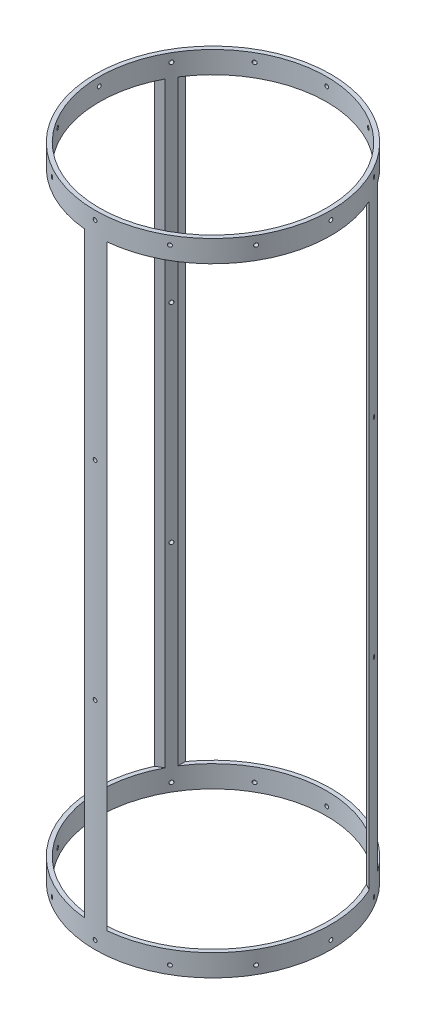
SolidWorks part; units mm, degrees
material "6061-T6 (SS)"
ref_plane "Front Plane" through (0, 0, 0) normal (0, 0, 1) x (1, 0, 0)
ref_plane "Top Plane" through (0, 0, 0) normal (0, 1, 0) x (1, 0, 0)
ref_plane "Right Plane" through (0, 0, 0) normal (1, 0, 0) x (0, 0, -1)
sketch "Sketch1" plane through (0, 0, 0) normal (0, 1, 0) x (1, 0, 0)
  circle A0 centre (0, 0) radius 88.9
  circle A1 centre (0, 0) radius 85.725
  dimension "D1" = 177.8
  dimension "D2" = 171.45
extrude "Boss-Extrude1" add sketch "Sketch1" along normal mid plane 482.854
sketch "Sketch2" plane through (0, 0, 0) normal (0, 0, 1) x (1, 0, 0)
  line L0 (85.725, 241.427) -> (-85.725, 241.427) construction
  line L1 (-72.39, -224.917) -> (72.39, -224.917)
  line L2 (-72.39, -224.917) -> (-72.39, 224.917)
  line L3 (-72.39, 224.917) -> (72.39, 224.917)
  line L4 (72.39, -224.917) -> (72.39, 224.917)
  line L5 (-72.39, -224.917) -> (72.39, 224.917) construction
  line L6 (-72.39, 224.917) -> (72.39, -224.917) construction
  line L7 (88.9, -241.427) -> (88.9, 241.427) construction
  point P0 (0, 0)
  dimension "D1" = 16.51
  dimension "D2" = 16.51
extrude "Cut-Extrude1" cut sketch "Sketch2" against normal up to surface (51.6033 mm away)
pattern_circular "CirPattern1" count 3 over 360 about axis through (0, 0, 0) along (0, 1, 0) of "Cut-Extrude1"
ref_plane "Plane1" through (88.9, 0, 0) normal (1, 0, 0) x (0, 0, -1)
sketch "Sketch4" plane through (88.9, 0, 0) normal (1, 0, 0) x (0, 0, -1)
  line L0 (0, 97.79) -> (0, -97.79) construction
  line L1 (88.9, 241.427) -> (-88.9, 241.427) construction
  circle A0 centre (0, 235.077) radius 1.4351
  dimension "D1" = 2.8702
  dimension "D2" = 6.35
extrude "Cut-Extrude3" cut sketch "Sketch4" against normal blind 15.24
pattern_circular "CirPattern3" count 12 over 360 about axis through (0, 241.427, 0) along (0, -1, 0) of "Cut-Extrude3"
mirror "Mirror1" about plane through (0, 0, 0) normal (0, 1, 0) of "Cut-Extrude3", "CirPattern3"
ref_plane "Plane2" through (0, 0, 88.9) normal (0, 0, 1) x (1, 0, 0)
sketch "Sketch5" plane through (0, 0, 88.9) normal (0, 0, 1) x (1, 0, 0)
  circle A0 centre (0, 78.359) radius 1.4351
  circle A1 centre (0, -78.359) radius 1.4351
  circle A2 centre (0, -235.077) radius 1.4351 construction
  circle A3 centre (0, 235.077) radius 1.4351 construction
  dimension "D1" = 156.718
  dimension "D2" = 156.718
  dimension "D3" = 2.8702
  dimension "D4" = 2.8702
extrude "Cut-Extrude4" cut sketch "Sketch5" against normal blind 22.86
pattern_circular "CirPattern4" count 3 over 360 about axis through (0, 241.427, 0) along (0, -1, 0) of "Cut-Extrude4"
